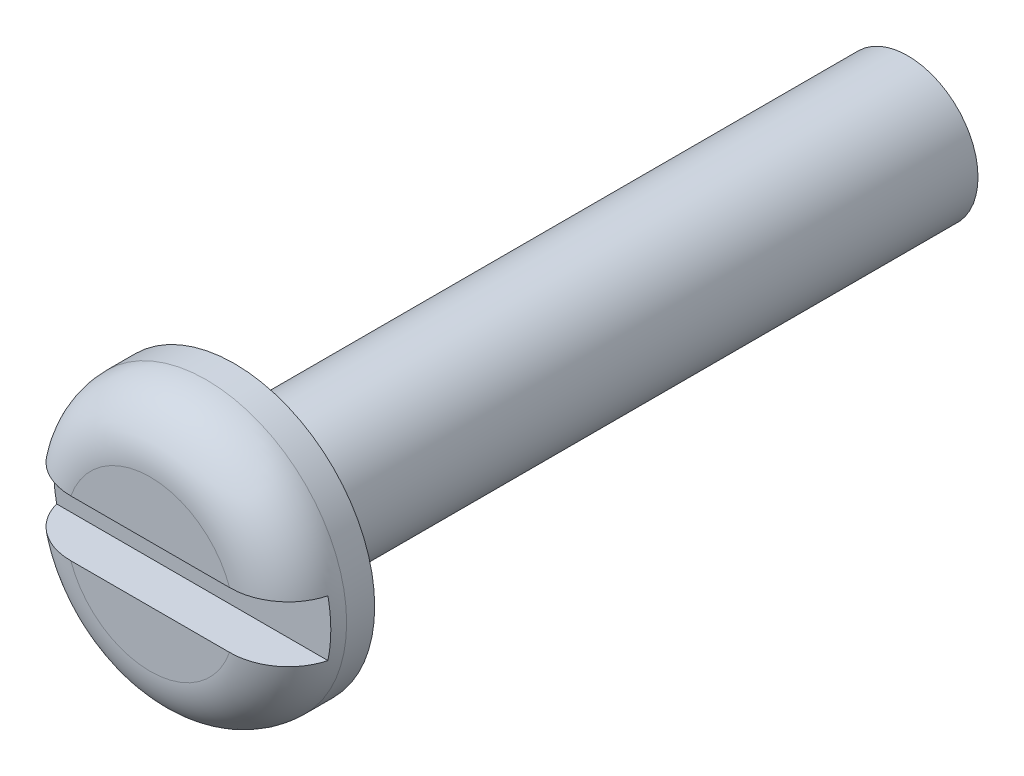
SolidWorks part; units mm, degrees
ref_plane "Front Plane" through (0, 0, 0) normal (0, 0, 1) x (1, 0, 0)
ref_plane "Top Plane" through (0, 0, 0) normal (0, 1, 0) x (1, 0, 0)
ref_plane "Right Plane" through (0, 0, 0) normal (1, 0, 0) x (0, 0, -1)
sketch "Sketch2" plane through (0, 0, 0) normal (0, 0, 1) x (1, 0, 0)
  circle A0 centre (0, 0) radius 1.25
extrude "Boss-Extrude1" add sketch "Sketch2" against normal blind 12
sketch "Sketch3" plane through (0, 0, 0) normal (0, 0, 1) x (1, 0, 0)
  circle A0 centre (0, 0) radius 2.5
extrude "Boss-Extrude2" add sketch "Sketch3" along normal blind 1.5
fillet "Fillet1" radius 1 1 edges at (2.5, 0, 1.5)
sketch "Sketch4" plane through (0, 0, 1.5) normal (0, 0, 1) x (1, 0, 0)
  line L1 (-3.1029, -0.5) -> (3.0053, -0.5)
  line L2 (-3.1029, -0.5) -> (-3.1029, 0.5)
  line L3 (-3.1029, 0.5) -> (3.0053, 0.5)
  line L4 (3.0053, -0.5) -> (3.0053, 0.5)
  dimension "D1" = 1
  dimension "D2" = 0.5
extrude "Cut-Extrude1" cut sketch "Sketch4" against normal blind 0.75
